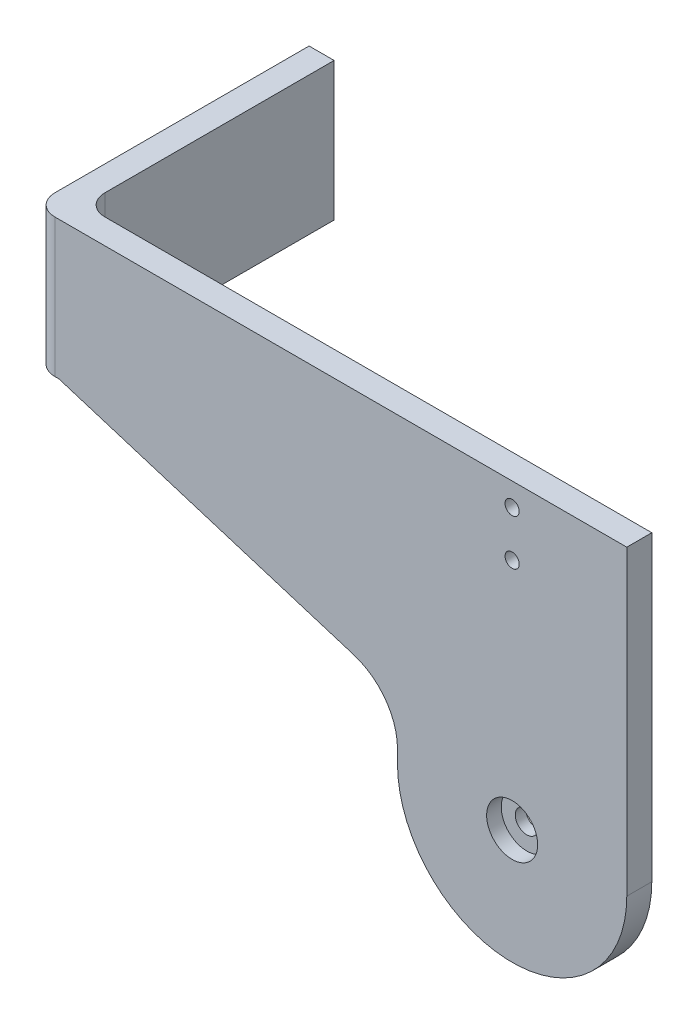
SolidWorks part; units mm, degrees
material "1023 al carbonio, lamiera (SS)"
ref_plane "Piano frontale" through (0, 0, 0) normal (0, 0, 1) x (1, 0, 0)
ref_plane "Piano superiore" through (0, 0, 0) normal (0, 1, 0) x (1, 0, 0)
ref_plane "Piano destro" through (0, 0, 0) normal (1, 0, 0) x (0, 0, -1)
sketch "Schizzo2" plane through (0, 0, 0) normal (0, 0, 1) x (1, 0, 0)
  line L0 (0, 0) -> (0, 45) construction
  line L1 (-27.5, 0) -> (-27.5, 45)
  line L2 (27.5, 0) -> (27.5, 45)
  arc A0 (-27.5, 0) -> (27.5, 0) centre (0, 0) ccw
  arc A1 (27.5, 45) -> (-27.5, 45) centre (0, 45) ccw
  point P3 (0, 22.5)
  point P8 (0, -27.5)
  point P9 (0, 72.5)
  dimension "D1" = 100
  dimension "D2" = 55
extrude "Estrusione-Estrusione1" add sketch "Schizzo2" along normal blind 6
sketch "Schizzo3" plane through (0, 0, 0) normal (0, 0, 1) x (1, 0, 0)
  line L1 (27.5, 0) -> (-108.7, 0)
  line L2 (27.5, 0) -> (27.5, 72.5)
  line L3 (27.5, 72.5) -> (-108.7, 72.5)
  line L4 (-108.7, 0) -> (-108.7, 72.5)
  arc A0 (27.5, 45) -> (-27.5, 45) centre (0, 45) ccw construction
  point P9 (0, 72.5)
  dimension "D1" = 136.2
  dimension "D2" = 72.5
  dimension "D3" = 72.5
extrude "Estrusione-Estrusione2" add sketch "Schizzo3" along normal blind 6
sketch "Schizzo4" plane through (0, 0, 6) normal (0, 0, 1) x (1, 0, 0)
  line L2 (-27.5, 0) -> (-108.7, 0)
  line L3 (-108.7, 0) -> (-108.7, 39.3472)
  line L4 (-108.7, 39.3472) -> (-27.5, 14.1424)
  line L5 (-27.5, 14.1424) -> (-27.5, 0)
  line L6 (-108.7, 72.5) -> (-108.7, 0) construction
extrude "Taglio-Estrusione1" cut sketch "Schizzo4" against normal through all
fillet "Raccordo5" radius 15 1 edges at (-27.5, 14.1424, 3)
sketch "Schizzo9" plane through (0, 0, 0) normal (0, 0, 1) x (1, 0, 0)
  line L0 (-108.7, 39.3472) -> (-114.7, 39.3472)
  line L1 (-114.7, 39.3472) -> (-114.7, 72.5)
  line L2 (-114.7, 72.5) -> (-108.7, 72.5)
  line L3 (-108.7, 72.5) -> (-108.7, 39.3472)
extrude "Estrusione-Estrusione5" add sketch "Schizzo9" against normal blind 60 and the other way up to vertex (6 mm away) other way up to point (-108.7, 72.5, 6)
fillet "Raccordo6" radius 5 1 edges at (-108.7, 55.9236, 0)
fillet "Raccordo7" radius 5 1 edges at (-114.7, 55.9236, 6)
sketch "Schizzo10" plane through (0, 0, 0) normal (0, 0, -1) x (-1, 0, 0)
  line L0 (0, 72.5) -> (0, 67) construction
  line L1 (-27.5, 72.5) -> (103.7, 72.5) construction
  line L2 (0, 67) -> (0, 56.05) construction
  dimension "D1" = 5.5
  dimension "D2" = 10.95
hole_wizard "Foro lamato per Bullone M3 a testa esagonale-3" positions "Schizzo19" profile "Schizzo20" size "M3" standard "GB" slot yes end condition through all
sketch "Schizzo19" plane through (0, 0, 0) normal (0, 0, -1) x (-1, 0, 0)
  point P0 (0, 67)
  point P3 (0, 56.05)
sketch "Schizzo20" plane through (0, 67, 0) normal (1, 0, 0) x (0, 1, 0)
  line L0 (0, 0) -> (0, 6)
  line L1 (0, 6) -> (1.7, 6)
  line L3 (1.7, 6) -> (1.7, 0.5)
  line L4 (4.5, 0.5) -> (1.7, 0.5)
  line L5 (4.5, 0.5) -> (4.5, 0.025)
  line L6 (4.5, 0.025) -> (4.525, 0)
  line L7 (4.525, 0) -> (0, 0)
  line L8 (-4.5, 0.025) -> (-4.525, 0) construction
  line L11 (0, -6.35) -> (0, 107.95) construction
  dimension "Thru Hole Dia." = 3.4
  dimension "Thru Hole Depth" = 6
  dimension "C'Bore Dia." = 9
  dimension "C'Bore Depth" = 0.5
  dimension "Near C'Sink Dia." = 9.05
  dimension "Near C'Sink Angle" = 90
hole_wizard "Foro lamato per Bullone M5 a testa esagonale-1" positions "Schizzo21" profile "Schizzo22" counterbore size "M5" standard "IS" end condition through all
sketch "Schizzo21" plane through (0, 0, 6) normal (0, 0, 1) x (1, 0, 0)
  point P0 (0, 0)
sketch "Schizzo22" plane through (0, 0, 6) normal (1, 0, 0) x (0, -1, 0)
  line L0 (0, 0) -> (0, 66)
  line L1 (0, 66) -> (2.75, 66)
  line L3 (2.75, 66) -> (2.75, 3.5)
  line L4 (2.75, 3.5) -> (6.119, 3.5)
  line L5 (6.119, 3.5) -> (6.119, 0)
  line L7 (6.119, 0) -> (0, 0)
  line L11 (0, -6.35) -> (0, 107.95) construction
  dimension "Thru Hole Dia." = 5.5
  dimension "Thru Hole Depth" = 66
  dimension "C'Bore Dia." = 12.238
  dimension "C'Bore Depth" = 3.5
